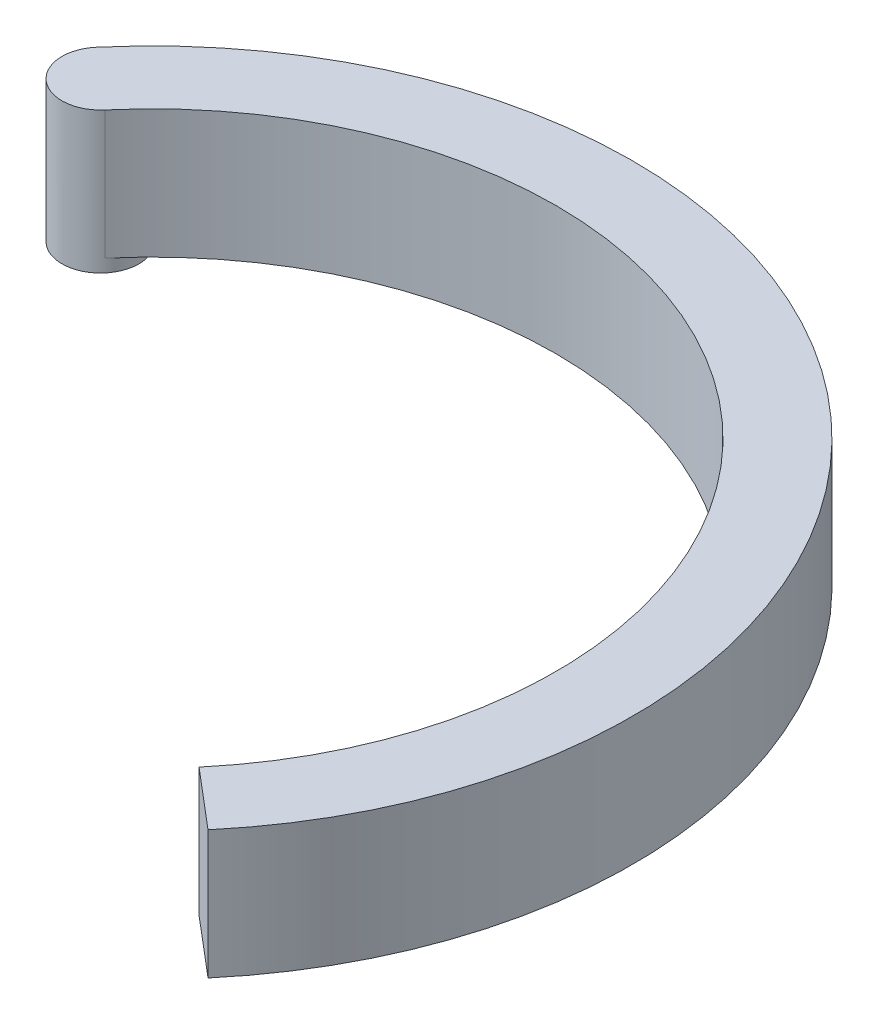
SolidWorks part; units mm, degrees
ref_plane "Front Plane" through (0, 0, 0) normal (0, 0, 1) x (1, 0, 0)
ref_plane "Top Plane" through (0, 0, 0) normal (0, 1, 0) x (1, 0, 0)
ref_plane "Right Plane" through (0, 0, 0) normal (1, 0, 0) x (0, 0, -1)
sketch "Sketch2" plane through (0, 0, 0) normal (0, 1, 0) x (1, 0, 0)
  arc A0 (0, 0) -> (52.5705, -44.5451) centre (26.2853, -22.2726) cw construction
  arc A1 (54.8593, -46.4846) -> (-2.2888, 1.9394) centre (26.2853, -22.2726) ccw
  arc A2 (50.2817, -42.6057) -> (2.2888, -1.9394) centre (26.2853, -22.2726) ccw
  arc A3 (50.2817, -42.6057) -> (54.8593, -46.4846) centre (52.5705, -44.5451) ccw
  arc A4 (-2.2888, 1.9394) -> (2.2888, -1.9394) centre (0, 0) ccw
  point P3 (48.5578, 4.0127)
extrude "Boss-Extrude1" add sketch "Sketch2" along normal blind 10
sketch "Sketch3" plane through (0, 0, 0) normal (0, -1, 0) x (1, 0, 0)
  circle A0 centre (0, 0) radius 3
extrude "Boss-Extrude2" add sketch "Sketch3" along normal blind 1
sketch "Sketch4" plane through (0, 0, 0) normal (0, -1, 0) x (1, 0, 0)
  line L0 (54.8593, 46.4846) -> (50.2817, 42.6057)
  arc A0 (50.2817, 42.6057) -> (50.6311, 46.834) centre (52.5705, 44.5451) cw
  arc A1 (54.8593, 46.4846) -> (50.2817, 42.6057) centre (52.5705, 44.5451) ccw construction
  arc A2 (50.6311, 46.834) -> (54.8593, 46.4846) centre (52.5705, 44.5451) cw
extrude "Cut-Extrude1" cut sketch "Sketch4" against normal blind 104 and the other way blind 59
